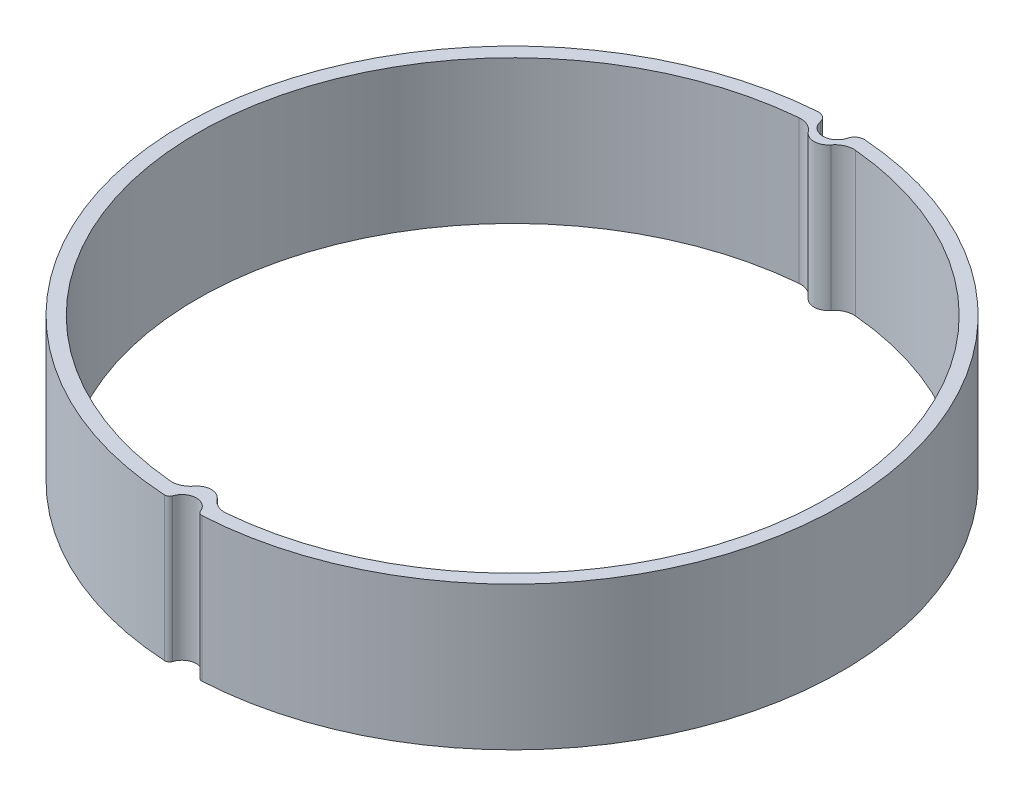
SolidWorks part; units mm, degrees
ref_plane "Front Plane" through (0, 0, 0) normal (0, 0, 1) x (1, 0, 0)
ref_plane "Top Plane" through (0, 0, 0) normal (0, 1, 0) x (1, 0, 0)
ref_plane "Right Plane" through (0, 0, 0) normal (1, 0, 0) x (0, 0, -1)
sketch "Sketch1" plane through (0, 0, 0) normal (0, 1, 0) x (1, 0, 0)
  line L3 (0, 0) -> (0, 3.1872) construction
  line L4 (0, 3.1872) -> (2.417, 3.1872)
  line L5 (0, 3.1872) -> (-2.417, 3.1872)
  arc A0 (1.8838, -34.3484) -> (34.3658, -1.5338) centre (0, 0) ccw
  circle A1 centre (0, 0) radius 37.4
  arc A2 (-2.417, 3.1872) -> (2.417, 3.1872) centre (0, 0) ccw
  circle A3 centre (0, 0) radius 34.4 construction
  arc A7 (-1.466, 33.6193) -> (1.4524, 33.5621) centre (0, 33.9371) ccw
  arc A8 (34.3658, -1.5338) -> (2.4931, 34.3095) centre (0, 0) ccw
  arc A9 (-2.5162, 34.4048) -> (-34.4624, -1.5388) centre (0, 0) ccw
  arc A10 (-34.4624, -1.5388) -> (-1.95, -34.4416) centre (0, 0) ccw
  arc A11 (1.4524, 33.5621) -> (2.4931, 34.3095) centre (2.4206, 33.3122) cw
  arc A12 (-1.466, 33.6193) -> (-2.5162, 34.4048) centre (-2.4433, 33.4075) ccw
  arc A13 (1.3882, -34.0245) -> (-1.4454, -34.0944) centre (-0.0165, -34.5507) ccw
  arc A14 (1.3882, -34.0245) -> (1.8838, -34.3484) centre (1.8564, -33.8491) ccw
  arc A15 (-1.4454, -34.0944) -> (-1.95, -34.4416) centre (-1.9217, -33.9424) cw
  point P0 (0, 0)
  point P15 (1.4997, 33.97)
  dimension "D2" = 4.834
  dimension "D3" = 4
  dimension "D4" = 34.4
  dimension "D5" = 1
  dimension "D6" = 1.5
  dimension "D7" = 0.5
  dimension "D8" = 1.5
  dimension "D9" = 1.9335
  dimension "D11" = 1.4997
sketch "Sketch2" plane through (0, 0, 0) normal (0, 1, 0) x (1, 0, 0)
  arc A0 (-32.8669, -2.9605) -> (-2.9605, -32.8669) centre (0, 0) ccw
  arc A1 (-1.1919, 32.0893) -> (1.1919, 32.0893) centre (0, 33) ccw
  arc A3 (1.1919, -32.0893) -> (-1.1919, -32.0893) centre (0, -33) ccw
  arc A5 (-2.9605, 32.8669) -> (-32.8669, -2.9605) centre (0, 0) ccw
  arc A6 (32.8669, -2.9605) -> (2.9605, 32.8669) centre (0, 0) ccw
  arc A7 (2.9605, -32.8669) -> (32.8669, -2.9605) centre (0, 0) ccw
  arc A10 (1.1919, -32.0893) -> (2.9605, -32.8669) centre (2.7811, -30.875) ccw
  arc A11 (-1.1919, -32.0893) -> (-2.9605, -32.8669) centre (-2.7811, -30.875) cw
  arc A14 (1.1919, 32.0893) -> (2.9605, 32.8669) centre (2.7811, 30.875) cw
  arc A15 (-1.1919, 32.0893) -> (-2.9605, 32.8669) centre (-2.7811, 30.875) ccw
  point P4 (0, 0)
  point P5 (0, 0)
  point P8 (0, 0)
  point P9 (0, 0)
  point P11 (0, 0)
  point P12 (0, 0)
  point P21 (1.4996, -32.9659)
  point P33 (-1.4996, 32.9659)
  dimension "D1" = 33
  dimension "D2" = 1.5
  dimension "D5" = 1.5
extrude "Boss-Extrude1" add sketch "Sketch1" along normal blind 15
extrude "Cut-Extrude2" cut sketch "Sketch2" along normal through all
